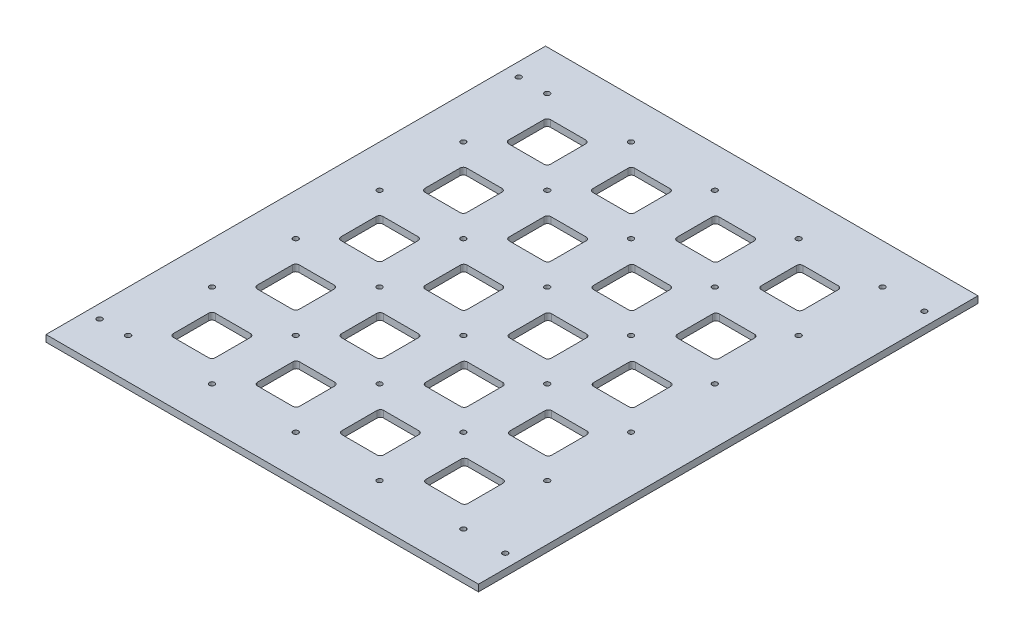
SolidWorks part; units mm, degrees
ref_plane "Front Plane" through (0, 0, 0) normal (0, 0, 1) x (1, 0, 0)
ref_plane "Top Plane" through (0, 0, 0) normal (0, 1, 0) x (1, 0, 0)
ref_plane "Right Plane" through (0, 0, 0) normal (1, 0, 0) x (0, 0, -1)
sketch "Sketch1" plane through (0, 0, 0) normal (0, 1, 0) x (1, 0, 0)
  line L0 (-258, 149) -> (0, 149) construction
  line L1 (-258, 298) -> (0, 298)
  line L2 (-258, 298) -> (-258, 0)
  line L3 (-258, 0) -> (0, 0)
  line L4 (0, 298) -> (0, 0)
  line L5 (-129, 298) -> (-129, 0) construction
  line L6 (-208, 261.5) -> (-208, 236.5) construction
  line L11 (-218.5, 261.5) -> (-197.5, 261.5)
  line L12 (-220.5, 259.5) -> (-220.5, 238.5)
  line L13 (-218.5, 236.5) -> (-197.5, 236.5)
  line L14 (-195.5, 259.5) -> (-195.5, 238.5)
  line L15 (-233, 274) -> (-183, 274) construction
  line L16 (-208, 274) -> (-208, 261.5) construction
  line L17 (-170.2738, 259.5) -> (-170.2738, 238.5)
  line L18 (-168.2738, 261.5) -> (-147.2738, 261.5)
  line L19 (-145.2738, 259.5) -> (-145.2738, 238.5)
  line L20 (-168.2738, 236.5) -> (-147.2738, 236.5)
  line L21 (-120.0476, 259.5) -> (-120.0476, 238.5)
  line L22 (-118.0476, 261.5) -> (-97.0476, 261.5)
  line L23 (-95.0476, 259.5) -> (-95.0476, 238.5)
  line L24 (-118.0476, 236.5) -> (-97.0476, 236.5)
  line L25 (-69.8214, 259.5) -> (-69.8214, 238.5)
  line L26 (-67.8214, 261.5) -> (-46.8214, 261.5)
  line L27 (-44.8214, 259.5) -> (-44.8214, 238.5)
  line L28 (-67.8214, 236.5) -> (-46.8214, 236.5)
  line L29 (-220.5, 209.5) -> (-220.5, 188.5)
  line L30 (-218.5, 211.5) -> (-197.5, 211.5)
  line L31 (-195.5, 209.5) -> (-195.5, 188.5)
  line L32 (-218.5, 186.5) -> (-197.5, 186.5)
  line L33 (-170.2738, 209.5) -> (-170.2738, 188.5)
  line L34 (-168.2738, 186.5) -> (-147.2738, 186.5)
  line L35 (-145.2738, 209.5) -> (-145.2738, 188.5)
  line L36 (-168.2738, 211.5) -> (-147.2738, 211.5)
  line L37 (-120.0476, 209.5) -> (-120.0476, 188.5)
  line L38 (-118.0476, 186.5) -> (-97.0476, 186.5)
  line L39 (-95.0476, 209.5) -> (-95.0476, 188.5)
  line L40 (-118.0476, 211.5) -> (-97.0476, 211.5)
  line L41 (-69.8214, 209.5) -> (-69.8214, 188.5)
  line L42 (-67.8214, 186.5) -> (-46.8214, 186.5)
  line L43 (-44.8214, 209.5) -> (-44.8214, 188.5)
  line L44 (-67.8214, 211.5) -> (-46.8214, 211.5)
  line L45 (-220.5, 159.5) -> (-220.5, 138.5)
  line L46 (-218.5, 161.5) -> (-197.5, 161.5)
  line L47 (-195.5, 159.5) -> (-195.5, 138.5)
  line L48 (-218.5, 136.5) -> (-197.5, 136.5)
  line L49 (-170.2738, 159.5) -> (-170.2738, 138.5)
  line L50 (-168.2738, 136.5) -> (-147.2738, 136.5)
  line L51 (-145.2738, 159.5) -> (-145.2738, 138.5)
  line L52 (-168.2738, 161.5) -> (-147.2738, 161.5)
  line L53 (-120.0476, 159.5) -> (-120.0476, 138.5)
  line L54 (-118.0476, 136.5) -> (-97.0476, 136.5)
  line L55 (-95.0476, 159.5) -> (-95.0476, 138.5)
  line L56 (-118.0476, 161.5) -> (-97.0476, 161.5)
  line L57 (-69.8214, 159.5) -> (-69.8214, 138.5)
  line L58 (-67.8214, 136.5) -> (-46.8214, 136.5)
  line L59 (-44.8214, 159.5) -> (-44.8214, 138.5)
  line L60 (-67.8214, 161.5) -> (-46.8214, 161.5)
  line L61 (-220.5, 109.5) -> (-220.5, 88.5)
  line L62 (-218.5, 111.5) -> (-197.5, 111.5)
  line L63 (-195.5, 109.5) -> (-195.5, 88.5)
  line L64 (-218.5, 86.5) -> (-197.5, 86.5)
  line L65 (-170.2738, 109.5) -> (-170.2738, 88.5)
  line L66 (-168.2738, 86.5) -> (-147.2738, 86.5)
  line L67 (-145.2738, 109.5) -> (-145.2738, 88.5)
  line L68 (-168.2738, 111.5) -> (-147.2738, 111.5)
  line L69 (-120.0476, 109.5) -> (-120.0476, 88.5)
  line L70 (-118.0476, 86.5) -> (-97.0476, 86.5)
  line L71 (-95.0476, 109.5) -> (-95.0476, 88.5)
  line L72 (-118.0476, 111.5) -> (-97.0476, 111.5)
  line L73 (-69.8214, 109.5) -> (-69.8214, 88.5)
  line L74 (-67.8214, 86.5) -> (-46.8214, 86.5)
  line L75 (-44.8214, 109.5) -> (-44.8214, 88.5)
  line L76 (-67.8214, 111.5) -> (-46.8214, 111.5)
  line L77 (-220.5, 59.5) -> (-220.5, 38.5)
  line L78 (-218.5, 61.5) -> (-197.5, 61.5)
  line L79 (-195.5, 59.5) -> (-195.5, 38.5)
  line L80 (-218.5, 36.5) -> (-197.5, 36.5)
  line L81 (-170.2738, 59.5) -> (-170.2738, 38.5)
  line L82 (-168.2738, 36.5) -> (-147.2738, 36.5)
  line L83 (-145.2738, 59.5) -> (-145.2738, 38.5)
  line L84 (-168.2738, 61.5) -> (-147.2738, 61.5)
  line L85 (-120.0476, 59.5) -> (-120.0476, 38.5)
  line L86 (-118.0476, 36.5) -> (-97.0476, 36.5)
  line L87 (-95.0476, 59.5) -> (-95.0476, 38.5)
  line L88 (-118.0476, 61.5) -> (-97.0476, 61.5)
  line L89 (-69.8214, 59.5) -> (-69.8214, 38.5)
  line L90 (-67.8214, 36.5) -> (-46.8214, 36.5)
  line L91 (-44.8214, 59.5) -> (-44.8214, 38.5)
  line L92 (-67.8214, 61.5) -> (-46.8214, 61.5)
  circle A0 centre (-250, 274) radius 1.55
  circle A2 centre (-8, 274) radius 1.55
  circle A4 centre (-8, 24) radius 1.55
  circle A7 centre (-250, 24) radius 1.55
  circle A8 centre (-233, 274) radius 1.55
  circle A9 centre (-233, 224) radius 1.55
  circle A10 centre (-233, 174) radius 1.55
  circle A11 centre (-233, 124) radius 1.55
  circle A12 centre (-233, 74) radius 1.55
  circle A13 centre (-233, 24) radius 1.55
  circle A14 centre (-183, 24) radius 1.55
  circle A15 centre (-183, 74) radius 1.55
  circle A16 centre (-183, 124) radius 1.55
  circle A17 centre (-183, 174) radius 1.55
  circle A18 centre (-183, 224) radius 1.55
  circle A19 centre (-183, 274) radius 1.55
  circle A20 centre (-133, 24) radius 1.55
  circle A21 centre (-133, 74) radius 1.55
  circle A22 centre (-133, 124) radius 1.55
  circle A23 centre (-133, 174) radius 1.55
  circle A24 centre (-133, 224) radius 1.55
  circle A25 centre (-133, 274) radius 1.55
  circle A26 centre (-83, 24) radius 1.55
  circle A27 centre (-83, 74) radius 1.55
  circle A28 centre (-83, 124) radius 1.55
  circle A29 centre (-83, 174) radius 1.55
  circle A30 centre (-83, 224) radius 1.55
  circle A31 centre (-83, 274) radius 1.55
  circle A32 centre (-33, 24) radius 1.55
  circle A33 centre (-33, 74) radius 1.55
  circle A34 centre (-33, 124) radius 1.55
  circle A35 centre (-33, 174) radius 1.55
  circle A36 centre (-33, 224) radius 1.55
  circle A37 centre (-33, 274) radius 1.55
  arc A38 (-197.5, 261.5) -> (-195.5, 259.5) centre (-197.5, 259.5) cw
  arc A39 (-197.5, 236.5) -> (-195.5, 238.5) centre (-197.5, 238.5) ccw
  arc A40 (-220.5, 238.5) -> (-218.5, 236.5) centre (-218.5, 238.5) ccw
  arc A41 (-220.5, 259.5) -> (-218.5, 261.5) centre (-218.5, 259.5) cw
  arc A42 (-170.2738, 259.5) -> (-168.2738, 261.5) centre (-168.2738, 259.5) cw
  arc A43 (-170.2738, 238.5) -> (-168.2738, 236.5) centre (-168.2738, 238.5) ccw
  arc A44 (-147.2738, 261.5) -> (-145.2738, 259.5) centre (-147.2738, 259.5) cw
  arc A45 (-147.2738, 236.5) -> (-145.2738, 238.5) centre (-147.2738, 238.5) ccw
  arc A46 (-120.0476, 259.5) -> (-118.0476, 261.5) centre (-118.0476, 259.5) cw
  arc A47 (-120.0476, 238.5) -> (-118.0476, 236.5) centre (-118.0476, 238.5) ccw
  arc A48 (-97.0476, 261.5) -> (-95.0476, 259.5) centre (-97.0476, 259.5) cw
  arc A49 (-97.0476, 236.5) -> (-95.0476, 238.5) centre (-97.0476, 238.5) ccw
  arc A50 (-69.8214, 259.5) -> (-67.8214, 261.5) centre (-67.8214, 259.5) cw
  arc A51 (-69.8214, 238.5) -> (-67.8214, 236.5) centre (-67.8214, 238.5) ccw
  arc A52 (-46.8214, 261.5) -> (-44.8214, 259.5) centre (-46.8214, 259.5) cw
  arc A53 (-46.8214, 236.5) -> (-44.8214, 238.5) centre (-46.8214, 238.5) ccw
  arc A54 (-220.5, 209.5) -> (-218.5, 211.5) centre (-218.5, 209.5) cw
  arc A55 (-220.5, 188.5) -> (-218.5, 186.5) centre (-218.5, 188.5) ccw
  arc A56 (-197.5, 211.5) -> (-195.5, 209.5) centre (-197.5, 209.5) cw
  arc A57 (-197.5, 186.5) -> (-195.5, 188.5) centre (-197.5, 188.5) ccw
  arc A58 (-170.2738, 188.5) -> (-168.2738, 186.5) centre (-168.2738, 188.5) ccw
  arc A59 (-147.2738, 186.5) -> (-145.2738, 188.5) centre (-147.2738, 188.5) ccw
  arc A60 (-147.2738, 211.5) -> (-145.2738, 209.5) centre (-147.2738, 209.5) cw
  arc A61 (-170.2738, 209.5) -> (-168.2738, 211.5) centre (-168.2738, 209.5) cw
  arc A62 (-120.0476, 188.5) -> (-118.0476, 186.5) centre (-118.0476, 188.5) ccw
  arc A63 (-97.0476, 186.5) -> (-95.0476, 188.5) centre (-97.0476, 188.5) ccw
  arc A64 (-97.0476, 211.5) -> (-95.0476, 209.5) centre (-97.0476, 209.5) cw
  arc A65 (-120.0476, 209.5) -> (-118.0476, 211.5) centre (-118.0476, 209.5) cw
  arc A66 (-69.8214, 188.5) -> (-67.8214, 186.5) centre (-67.8214, 188.5) ccw
  arc A67 (-46.8214, 186.5) -> (-44.8214, 188.5) centre (-46.8214, 188.5) ccw
  arc A68 (-46.8214, 211.5) -> (-44.8214, 209.5) centre (-46.8214, 209.5) cw
  arc A69 (-69.8214, 209.5) -> (-67.8214, 211.5) centre (-67.8214, 209.5) cw
  arc A70 (-220.5, 159.5) -> (-218.5, 161.5) centre (-218.5, 159.5) cw
  arc A71 (-220.5, 138.5) -> (-218.5, 136.5) centre (-218.5, 138.5) ccw
  arc A72 (-197.5, 161.5) -> (-195.5, 159.5) centre (-197.5, 159.5) cw
  arc A73 (-197.5, 136.5) -> (-195.5, 138.5) centre (-197.5, 138.5) ccw
  arc A74 (-170.2738, 138.5) -> (-168.2738, 136.5) centre (-168.2738, 138.5) ccw
  arc A75 (-147.2738, 136.5) -> (-145.2738, 138.5) centre (-147.2738, 138.5) ccw
  arc A76 (-147.2738, 161.5) -> (-145.2738, 159.5) centre (-147.2738, 159.5) cw
  arc A77 (-170.2738, 159.5) -> (-168.2738, 161.5) centre (-168.2738, 159.5) cw
  arc A78 (-120.0476, 138.5) -> (-118.0476, 136.5) centre (-118.0476, 138.5) ccw
  arc A79 (-97.0476, 136.5) -> (-95.0476, 138.5) centre (-97.0476, 138.5) ccw
  arc A80 (-97.0476, 161.5) -> (-95.0476, 159.5) centre (-97.0476, 159.5) cw
  arc A81 (-120.0476, 159.5) -> (-118.0476, 161.5) centre (-118.0476, 159.5) cw
  arc A82 (-69.8214, 138.5) -> (-67.8214, 136.5) centre (-67.8214, 138.5) ccw
  arc A83 (-46.8214, 136.5) -> (-44.8214, 138.5) centre (-46.8214, 138.5) ccw
  arc A84 (-46.8214, 161.5) -> (-44.8214, 159.5) centre (-46.8214, 159.5) cw
  arc A85 (-69.8214, 159.5) -> (-67.8214, 161.5) centre (-67.8214, 159.5) cw
  arc A86 (-220.5, 109.5) -> (-218.5, 111.5) centre (-218.5, 109.5) cw
  arc A87 (-220.5, 88.5) -> (-218.5, 86.5) centre (-218.5, 88.5) ccw
  arc A88 (-197.5, 111.5) -> (-195.5, 109.5) centre (-197.5, 109.5) cw
  arc A89 (-197.5, 86.5) -> (-195.5, 88.5) centre (-197.5, 88.5) ccw
  arc A90 (-170.2738, 88.5) -> (-168.2738, 86.5) centre (-168.2738, 88.5) ccw
  arc A91 (-147.2738, 86.5) -> (-145.2738, 88.5) centre (-147.2738, 88.5) ccw
  arc A92 (-147.2738, 111.5) -> (-145.2738, 109.5) centre (-147.2738, 109.5) cw
  arc A93 (-170.2738, 109.5) -> (-168.2738, 111.5) centre (-168.2738, 109.5) cw
  arc A94 (-120.0476, 88.5) -> (-118.0476, 86.5) centre (-118.0476, 88.5) ccw
  arc A95 (-97.0476, 86.5) -> (-95.0476, 88.5) centre (-97.0476, 88.5) ccw
  arc A96 (-97.0476, 111.5) -> (-95.0476, 109.5) centre (-97.0476, 109.5) cw
  arc A97 (-120.0476, 109.5) -> (-118.0476, 111.5) centre (-118.0476, 109.5) cw
  arc A98 (-69.8214, 88.5) -> (-67.8214, 86.5) centre (-67.8214, 88.5) ccw
  arc A99 (-46.8214, 86.5) -> (-44.8214, 88.5) centre (-46.8214, 88.5) ccw
  arc A100 (-46.8214, 111.5) -> (-44.8214, 109.5) centre (-46.8214, 109.5) cw
  arc A101 (-69.8214, 109.5) -> (-67.8214, 111.5) centre (-67.8214, 109.5) cw
  arc A102 (-220.5, 59.5) -> (-218.5, 61.5) centre (-218.5, 59.5) cw
  arc A103 (-220.5, 38.5) -> (-218.5, 36.5) centre (-218.5, 38.5) ccw
  arc A104 (-197.5, 61.5) -> (-195.5, 59.5) centre (-197.5, 59.5) cw
  arc A105 (-197.5, 36.5) -> (-195.5, 38.5) centre (-197.5, 38.5) ccw
  arc A106 (-170.2738, 38.5) -> (-168.2738, 36.5) centre (-168.2738, 38.5) ccw
  arc A107 (-147.2738, 36.5) -> (-145.2738, 38.5) centre (-147.2738, 38.5) ccw
  arc A108 (-147.2738, 61.5) -> (-145.2738, 59.5) centre (-147.2738, 59.5) cw
  arc A109 (-170.2738, 59.5) -> (-168.2738, 61.5) centre (-168.2738, 59.5) cw
  arc A110 (-120.0476, 38.5) -> (-118.0476, 36.5) centre (-118.0476, 38.5) ccw
  arc A111 (-97.0476, 36.5) -> (-95.0476, 38.5) centre (-97.0476, 38.5) ccw
  arc A112 (-97.0476, 61.5) -> (-95.0476, 59.5) centre (-97.0476, 59.5) cw
  arc A113 (-120.0476, 59.5) -> (-118.0476, 61.5) centre (-118.0476, 59.5) cw
  arc A114 (-69.8214, 38.5) -> (-67.8214, 36.5) centre (-67.8214, 38.5) ccw
  arc A115 (-46.8214, 36.5) -> (-44.8214, 38.5) centre (-46.8214, 38.5) ccw
  arc A116 (-46.8214, 61.5) -> (-44.8214, 59.5) centre (-46.8214, 59.5) cw
  arc A117 (-69.8214, 59.5) -> (-67.8214, 61.5) centre (-67.8214, 59.5) cw
  point P85 (-195.5, 236.5)
  point P88 (-220.5, 236.5)
  dimension "D3" = 3.1
  dimension "D8" = 3.1
  dimension "D12" = 2
  dimension "D1" = 258
  dimension "D2" = 298
  dimension "D4" = 24
  dimension "D5" = 8
  dimension "D6" = 24
  dimension "D7" = 25
  dimension "D11" = 25
  dimension "D13" = 12.5
  dimension "D15" = 50
  dimension "D9" = 6
  dimension "D10" = 5
  dimension "D14" = 4
  dimension "D16" = 5
extrude "Boss-Extrude1" add sketch "Sketch1" along normal blind 4
equation "\"M3_hole_diameter\"= 3.1mm"
equation "\"﻿cf_tube_outer_diameter\"= 25mm"
equation "\"cf_tube_inner_diameter\" = 21mm"
equation "\"mid_plate_mid_to_top\" = 100mm"
equation "\"mid_plate_mid_to_bottom\" = 30mm"
equation "\"mid_plate_horizontal_spacing\"=250mm"
equation "\"cf_plate_thickness\" =4mm"
equation "\"mid_tube_length\" = 121mm"
equation "\"mid_support_plate_distance\" = 250mm"
equation "\"mid_plate_bottom_width\" = 180mm"
equation "\"nut_strip_2_hole_distance\" = 7mm"
equation "\"nut_strip_hole_diameter\" = 2.5mm"
